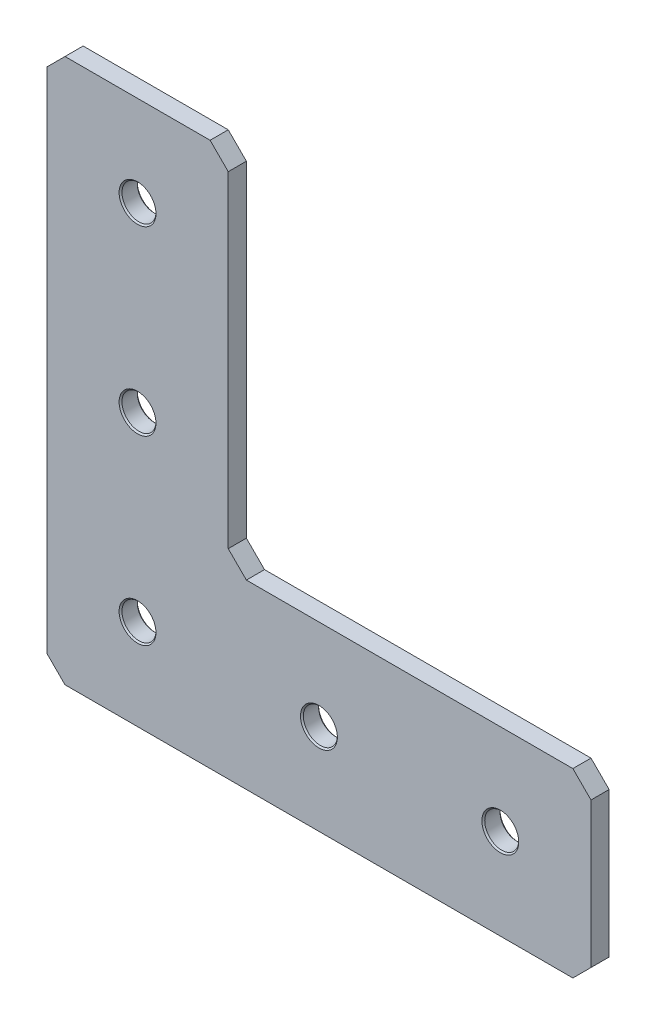
SolidWorks part; units mm, degrees
ref_plane "Front Plane" through (0, 0, 0) normal (0, 0, 1) x (1, 0, 0)
ref_plane "Top Plane" through (0, 0, 0) normal (0, 1, 0) x (1, 0, 0)
ref_plane "Right Plane" through (0, 0, 0) normal (1, 0, 0) x (0, 0, -1)
sketch "Sketch1" plane through (0, 0, 0) normal (0, 0, 1) x (1, 0, 0)
  line L2 (0, 0) -> (0, 50.8)
  line L3 (0, 50.8) -> (-25.4, 50.8)
  line L4 (-25.4, 0) -> (-25.4, 50.8)
  line L5 (0, 0) -> (50.8, 0)
  line L6 (-25.4, 0) -> (-25.4, -25.4)
  line L7 (-25.4, -25.4) -> (50.8, -25.4)
  line L8 (50.8, 0) -> (50.8, -25.4)
  dimension "D1" = 25.4
  dimension "D2" = 25.4
  dimension "D3" = 76.2
  dimension "D4" = 76.2
extrude "Boss-Extrude1" add sketch "Sketch1" along normal blind 2.54
hole_wizard "3/16 (0.1875) Diameter Hole1" positions "Sketch3" profile "Sketch2" hole size "3/16" standard "ANSI Inch" end condition through all
sketch "Sketch3" plane through (0, 0, 2.54) normal (0, 0, 1) x (1, 0, 0)
  line L0 (-12.7, 50.8) -> (-12.7, -25.4) construction
  line L1 (0, 50.8) -> (-25.4, 50.8) construction
  line L2 (-25.4, -25.4) -> (50.8, -25.4) construction
  line L3 (50.8, -12.7) -> (-25.4, -12.7) construction
  line L4 (50.8, -25.4) -> (50.8, 0) construction
  line L5 (-25.4, 50.8) -> (-25.4, -25.4) construction
  point P14 (-12.7, 38.1)
  point P16 (-12.7, 12.7)
  point P18 (-12.7, -12.7)
  point P20 (12.7, -12.7)
  point P22 (38.1, -12.7)
  dimension "D1" = 38.1
  dimension "D2" = 12.7
  dimension "D3" = 12.7
  dimension "D4" = 38.1
  dimension "D5" = 12.7
sketch "Sketch2" plane through (-12.7, 38.1, 2.54) normal (1, 0, 0) x (0, -1, 0)
  line L0 (0, 0) -> (0, 2.54)
  line L1 (0, 2.54) -> (2.3812, 2.54)
  line L2 (2.3812, 2.54) -> (2.3812, 0)
  line L5 (2.3812, 0) -> (0, 0)
  line L11 (0, -6.35) -> (0, 107.95) construction
  dimension "Thru Hole Dia." = 4.7625
  dimension "Thru Hole Depth" = 2.54
chamfer "Chamfer1" distance 2.54 angle 45 6 edges at (-25.4, -25.4, 1.27) (50.8, -25.4, 1.27) (50.8, 0, 1.27) (0, 0, 1.27) (0, 50.8, 1.27) (-25.4, 50.8, 1.27)
chamfer "Chamfer2" distance 0.2 angle 45 10 edges at (-10.3188, 38.1, 0) (-10.3188, 12.7, 0) (-10.3188, -12.7, 0) (15.0812, -12.7, 0) (40.4812, -12.7, 0) (40.4812, -12.7, 2.54) (15.0812, -12.7, 2.54) (-10.3188, -12.7, 2.54) (-10.3188, 12.7, 2.54) (-10.3188, 38.1, 2.54)
